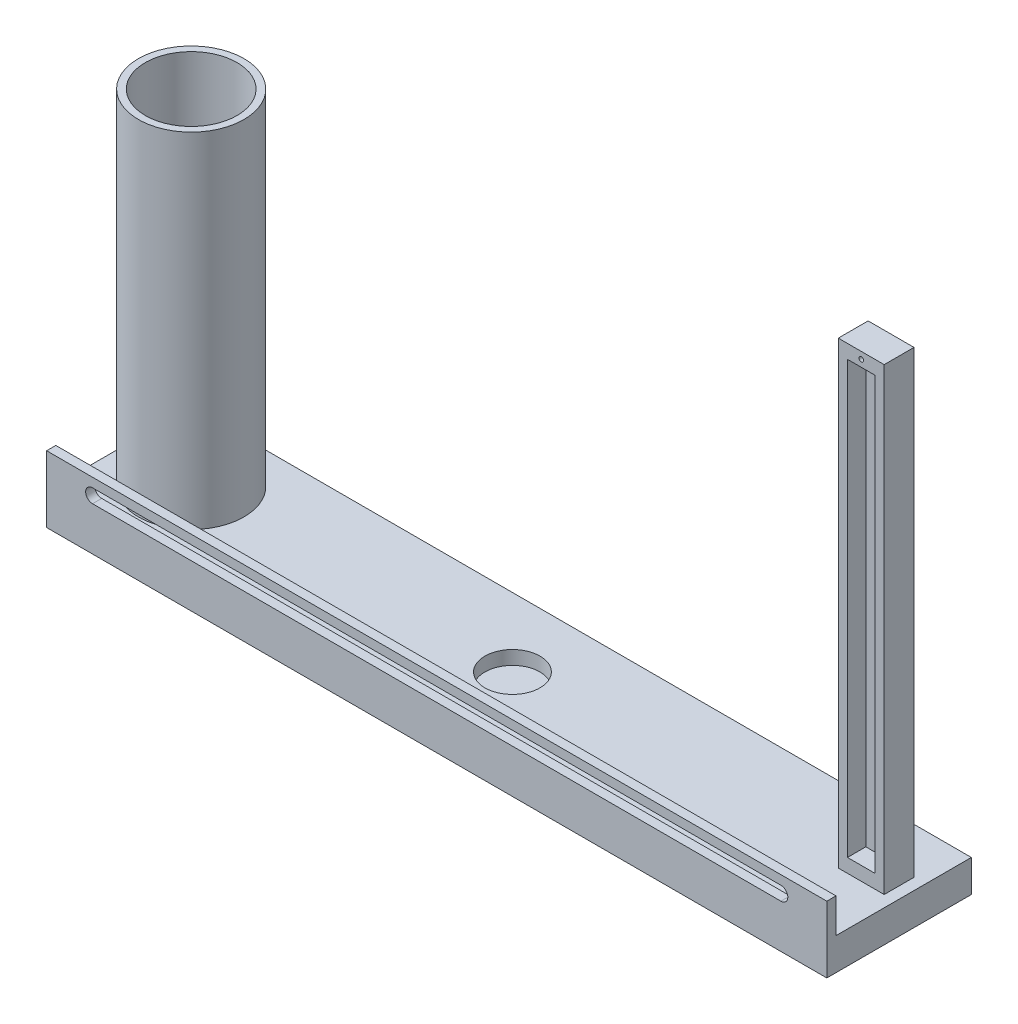
SolidWorks part; units mm, degrees
ref_plane "Front Plane" through (0, 0, 0) normal (0, 0, 1) x (1, 0, 0)
ref_plane "Top Plane" through (0, 0, 0) normal (0, 1, 0) x (1, 0, 0)
ref_plane "Right Plane" through (0, 0, 0) normal (1, 0, 0) x (0, 0, -1)
ref_plane "Plane1" through (0, 0, 0) normal (0, -1, 0) x (1, 0, 0)
sketch "Sketch1" plane through (0, 0, 0) normal (0, -1, 0) x (1, 0, 0)
  line L0 (0, 0) -> (0, -31.5)
  line L1 (0, -31.5) -> (170, -31.5)
  line L2 (170, -31.5) -> (170, 0)
  line L3 (170, 0) -> (0, 0)
extrude "Boss-Extrude1" add sketch "Sketch1" against normal blind 14.5
sketch "Sketch2" plane through (170, 0, 0) normal (1, 0, 0) x (0, 0, -1)
  line L0 (2, 7) -> (31.5, 7)
  line L1 (31.5, 7) -> (31.5, 14.5)
  line L2 (31.5, 14.5) -> (2, 14.5)
  line L3 (2, 14.5) -> (2, 7)
extrude "Cut-Extrude1" cut sketch "Sketch2" against normal through all
sketch "Sketch3" plane through (0, 0, 0) normal (0, 0, 1) x (1, 0, 0)
  line L0 (160, 12.5) -> (10, 12.5)
  line L1 (10, 9.5) -> (160, 9.5)
  arc A0 (10, 12.5) -> (10, 9.5) centre (10, 11) ccw
  arc A1 (160, 9.5) -> (160, 12.5) centre (160, 11) ccw
extrude "Cut-Extrude2" cut sketch "Sketch3" against normal through all
sketch "Sketch4" plane through (0, 7, 0) normal (0, 1, 0) x (-1, 0, 0)
  line L0 (-157.5, -15) -> (-157.5, -21.5)
  line L1 (-157.5, -21.5) -> (-167.5, -21.5)
  line L2 (-167.5, -21.5) -> (-167.5, -15)
  line L3 (-167.5, -15) -> (-157.5, -15)
extrude "Boss-Extrude2" add sketch "Sketch4" along normal blind 100
sketch "Sketch5" plane through (0, 0, -15) normal (0, 0, 1) x (1, 0, 0)
  line L0 (165.5, 104) -> (159.5, 104)
  line L1 (159.5, 104) -> (159.5, 10)
  line L2 (159.5, 10) -> (165.5, 10)
  line L3 (165.5, 10) -> (165.5, 104)
extrude "Cut-Extrude3" cut sketch "Sketch5" against normal blind 4
ref_plane "Plane2" through (0, 0, -16.5) normal (0, 0, 1) x (1, 0, 0)
sketch "Sketch6" plane through (0, 0, -16.5) normal (0, 0, 1) x (1, 0, 0)
  line L0 (26.5, 82) -> (15, 82)
  line L1 (15, 82) -> (15, 7)
  line L2 (15, 7) -> (26.5, 7)
  line L3 (26.5, 7) -> (26.5, 82)
  line L4 (15, 82) -> (15, 7) construction
revolve "Revolve1" add sketch "Sketch6" angle 360 about L4
hole_wizard "Ø12.0 (12) Diameter Hole1" positions "Sketch8" profile "Sketch7" hole size "Ø12.0" standard "ANSI Metric"
sketch "Sketch8" plane through (0, 7, 0) normal (0, 1, 0) x (1, 0, 0)
  point P0 (85, 16.5)
sketch "Sketch7" plane through (85, 7, -16.5) normal (1, 0, 0) x (0, 0, 1)
  line L0 (0, 0) -> (0, 3)
  line L1 (0, 3) -> (6, 3)
  line L2 (6, 3) -> (6, 0)
  line L5 (6, 0) -> (0, 0)
  line L10 (0, 3) -> (-6, 3) construction
  line L11 (0, -6.35) -> (0, 107.95) construction
  dimension "Hole Dia." = 12
  dimension "Hole Depth" = 3
  dimension "Drill Angle" = 180
hole_wizard "Ø1.0 (1) Diameter Hole1" positions "Sketch10" profile "Sketch9" hole size "Ø1.0" standard "ANSI Metric"
sketch "Sketch10" plane through (0, 0, -15) normal (0, 0, 1) x (1, 0, 0)
  point P0 (162.5, 105.5)
sketch "Sketch9" plane through (162.5, 105.5, -15) normal (1, 0, 0) x (0, -1, 0)
  line L0 (0, 0) -> (0, 1)
  line L1 (0, 1) -> (0.5, 1)
  line L2 (0.5, 1) -> (0.5, 0)
  line L5 (0.5, 0) -> (0, 0)
  line L10 (0, 1) -> (-0.5, 1) construction
  line L11 (0, -6.35) -> (0, 107.95) construction
  dimension "Hole Dia." = 1
  dimension "Hole Depth" = 1
  dimension "Drill Angle" = 180
hole_wizard "Ø20.0 (20) Diameter Hole1" positions "Sketch12" profile "Sketch11" hole size "Ø20.0" standard "ANSI Metric"
sketch "Sketch12" plane through (0, 82, 0) normal (0, 1, 0) x (1, 0, 0)
  point P0 (15, 16.5)
sketch "Sketch11" plane through (15, 82, -16.5) normal (1, 0, 0) x (0, 0, 1)
  line L0 (0, 0) -> (0, 79)
  line L1 (0, 79) -> (10, 79)
  line L2 (10, 79) -> (10, 0)
  line L5 (10, 0) -> (0, 0)
  line L10 (0, 79) -> (-10, 79) construction
  line L11 (0, -6.35) -> (0, 107.95) construction
  dimension "Hole Dia." = 20
  dimension "Hole Depth" = 79
  dimension "Drill Angle" = 180
